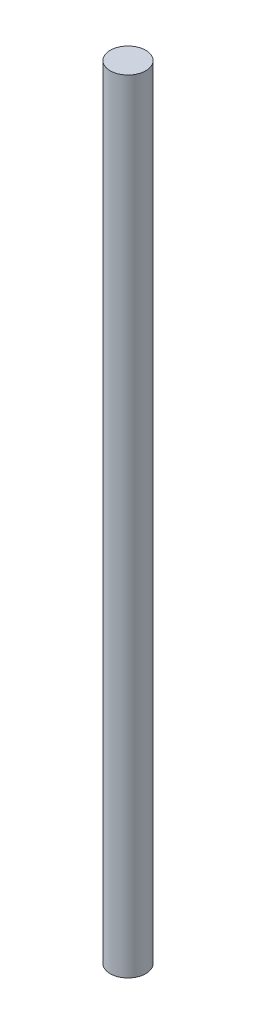
SolidWorks part; units mm, degrees
ref_plane "Front Plane" through (0, 0, 0) normal (0, 0, 1) x (1, 0, 0)
ref_plane "Top Plane" through (0, 0, 0) normal (0, 1, 0) x (1, 0, 0)
ref_plane "Right Plane" through (0, 0, 0) normal (1, 0, 0) x (0, 0, -1)
sketch "Sketch1" plane through (0, 0, 0) normal (0, 1, 0) x (1, 0, 0)
  circle A0 centre (0, 0) radius 2.5
  dimension "D1" = 5
extrude "Boss-Extrude1" add sketch "Sketch1" along normal mid plane 110
